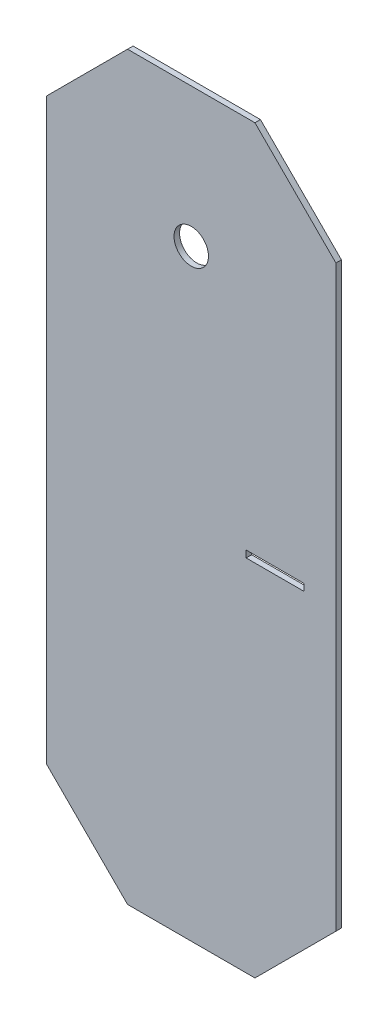
SolidWorks part; units mm, degrees
ref_plane "Спереди" through (0, 0, 0) normal (0, 0, 1) x (1, 0, 0)
ref_plane "Сверху" through (0, 0, 0) normal (0, 1, 0) x (1, 0, 0)
ref_plane "Справа" through (0, 0, 0) normal (1, 0, 0) x (0, 0, -1)
sketch "Эскиз1" plane through (0, 0, 0) normal (0, 0, 1) x (1, 0, 0)
  line L0 (-105, 539.9964) -> (-105, 203.9939)
  line L1 (105, 539.9964) -> (105, 203.9939)
  line L2 (0, 639.9964) -> (0, 656.3633) construction
  line L3 (46.2224, 640.7741) -> (-46.2224, 640.7741)
  line L4 (-105, 539.9964) -> (-105, 581.9964)
  line L5 (-105, 581.9964) -> (-46.2224, 640.7741)
  line L6 (105, 539.9964) -> (105, 581.9964)
  line L7 (105, 581.9964) -> (46.2224, 640.7741)
  line L8 (-100, 371.9952) -> (-247.0361, 371.9952) construction
  line L9 (105, 203.9939) -> (105, 161.9939)
  line L10 (105, 161.9939) -> (46.2224, 103.2162)
  line L11 (46.2224, 103.2162) -> (-46.2224, 103.2162)
  line L12 (-105, 161.9939) -> (-46.2224, 103.2162)
  line L13 (-105, 203.9939) -> (-105, 161.9939)
  circle A3 centre (0, 539.9964) radius 12.5
extrude "Вытянуть1" add sketch "Эскиз1" along normal blind 4
sketch "Эскиз2" plane through (0, 0, 4) normal (0, 0, 1) x (1, 0, 0)
  line L0 (39.8514, 366.5362) -> (61.7043, 366.5362) construction
  line L2 (60.9246, 374.2823) -> (60.9246, 384.1528) construction
  line L5 (39.8283, 369.0362) -> (81.9978, 369.0362)
  line L6 (39.8283, 369.0362) -> (39.8283, 364.0362)
  line L7 (39.8283, 364.0362) -> (81.9978, 364.0362)
  line L8 (81.9978, 369.0362) -> (81.9978, 364.0362)
  line L9 (39.8283, 369.0362) -> (81.9978, 364.0362) construction
  line L10 (39.8283, 364.0362) -> (81.9978, 369.0362) construction
  point P2 (60.913, 366.5362)
extrude "Вырез-Вытянуть1" cut sketch "Эскиз2" against normal through all
